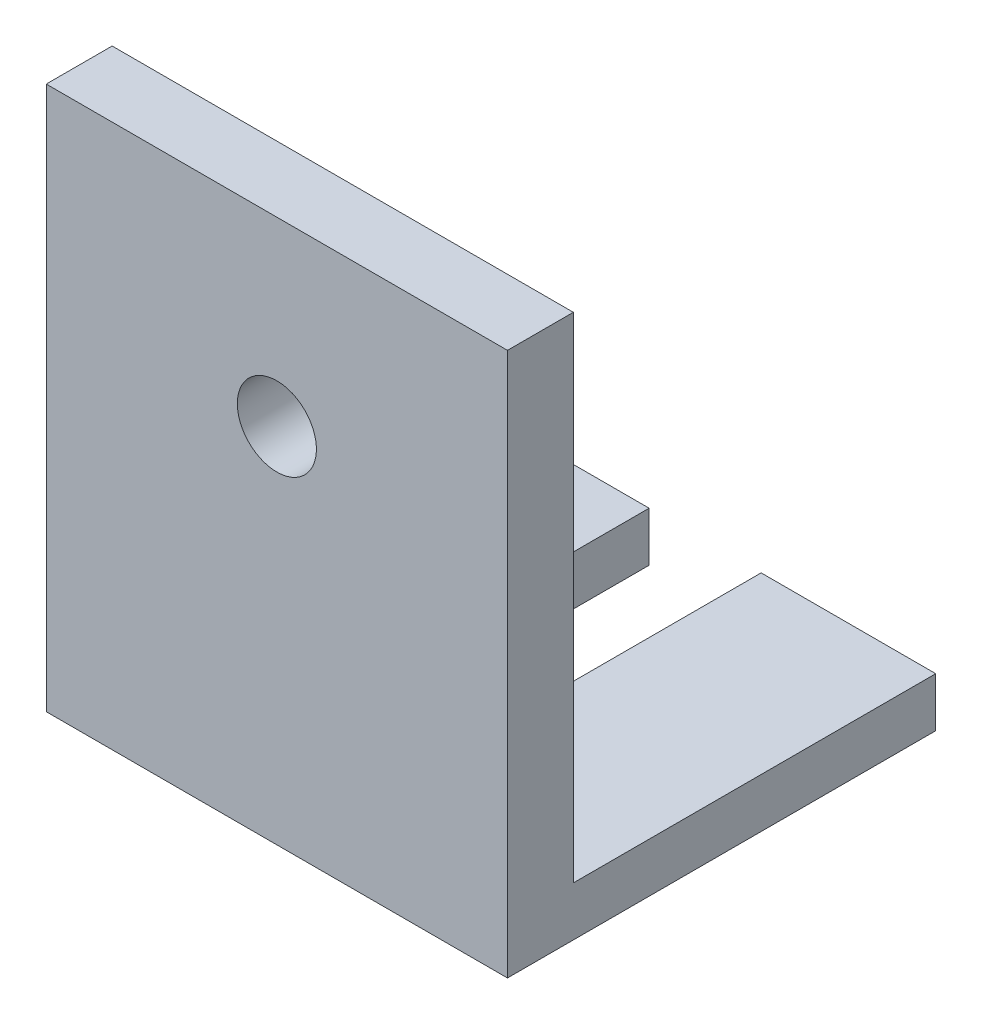
SolidWorks part; units mm, degrees
ref_plane "Front Plane" through (0, 0, 0) normal (0, 0, 1) x (1, 0, 0)
ref_plane "Top Plane" through (0, 0, 0) normal (0, 1, 0) x (1, 0, 0)
ref_plane "Right Plane" through (0, 0, 0) normal (1, 0, 0) x (0, 0, -1)
sketch "Sketch1" plane through (0, 0, 0) normal (0, 1, 0) x (1, 0, 0)
  line L1 (0, 0) -> (28, 0)
  line L2 (0, 0) -> (0, -28)
  line L3 (0, -28) -> (28, -28)
  line L4 (28, 0) -> (28, -28)
  dimension "D1" = 28
  dimension "D2" = 28
extrude "Boss-Extrude1" add sketch "Sketch1" along normal blind 25
sketch "Sketch2" plane through (0, 25, 0) normal (0, 1, 0) x (1, 0, 0)
  line L0 (28, -28) -> (28, 0) construction
  line L1 (0, 0) -> (28, 0)
  line L2 (0, 0) -> (0, -22)
  line L3 (0, -22) -> (28, -22)
  line L4 (28, 0) -> (28, -22)
  dimension "D1" = 22
extrude "Cut-Extrude1" cut sketch "Sketch2" against normal blind 22
sketch "Sketch3" plane through (0, 3, 0) normal (0, 1, 0) x (1, 0, 0)
  line L0 (28, 0) -> (0, 0) construction
  line L1 (10.6, 0) -> (17.4, 0)
  line L2 (10.6, 0) -> (10.6, -22)
  line L3 (10.6, -22) -> (17.4, -22)
  line L4 (17.4, 0) -> (17.4, -22)
  line L5 (0, -22) -> (28, -22) construction
  line L6 (0, 0) -> (0, -22) construction
  line L7 (28, -22) -> (28, 0) construction
  dimension "D1" = 6.8
  dimension "D2" = 22
  dimension "D3" = 10.6
  dimension "D4" = 10.6
extrude "Cut-Extrude2" cut sketch "Sketch3" against normal through all
sketch "Sketch4" plane through (0, 0, 22) normal (0, 0, -1) x (-1, 0, 0)
  line L0 (-10.6, 0) -> (-17.4, 0) construction
  line L1 (-28, 3) -> (-28, 25) construction
  line L2 (0, 3) -> (0, 25) construction
  circle A0 centre (-14, 10) radius 2.4
  dimension "D1" = 4.8
  dimension "D2" = 10
  dimension "D3" = 14
  dimension "D4" = 14
extrude "Cut-Extrude3" cut sketch "Sketch4" against normal through all
sketch "Sketch5" plane through (0, 25, 0) normal (0, 1, 0) x (1, 0, 0)
  line L1 (0, -28) -> (28, -28)
  line L2 (0, -28) -> (0, -22)
  line L3 (0, -22) -> (28, -22)
  line L4 (28, -28) -> (28, -22)
extrude "Cut-Extrude4" cut sketch "Sketch5" against normal blind 4
sketch "Sketch6" plane through (28, 0, 0) normal (1, 0, 0) x (0, 0, -1)
  line L0 (-28, 21) -> (-22, 21) construction
  line L1 (-28, 0) -> (-26, 0)
  line L2 (-28, 0) -> (-28, 21)
  line L3 (-28, 21) -> (-26, 21)
  line L4 (-26, 0) -> (-26, 21)
  dimension "D1" = 21
  dimension "D2" = 2
extrude "Cut-Extrude5" cut sketch "Sketch6" against normal through all
sketch "Sketch7" plane through (0, 0, 0) normal (0, -1, 0) x (1, 0, 0)
  line L1 (0, 26) -> (28, 26)
  line L2 (0, 26) -> (0, 0)
  line L3 (0, 0) -> (28, 0)
  line L4 (28, 26) -> (28, 0)
extrude "Boss-Extrude2" add sketch "Sketch7" along normal blind 12
sketch "Sketch9" plane through (0, 0, 0) normal (0, 1, 0) x (1, 0, 0)
  line L1 (10.6, 0) -> (17.4, 0)
  line L2 (10.6, 0) -> (10.6, -22)
  line L3 (10.6, -22) -> (17.4, -22)
  line L4 (17.4, 0) -> (17.4, -22)
extrude "Cut-Extrude6" cut sketch "Sketch9" against normal blind 12
sketch "Sketch10" plane through (0, 3, 0) normal (0, 1, 0) x (1, 0, 0)
  line L1 (0, 0) -> (28, 0)
  line L2 (0, 0) -> (0, -22)
  line L3 (0, -22) -> (28, -22)
  line L4 (28, 0) -> (28, -22)
extrude "Cut-Extrude7" cut sketch "Sketch10" against normal blind 12
